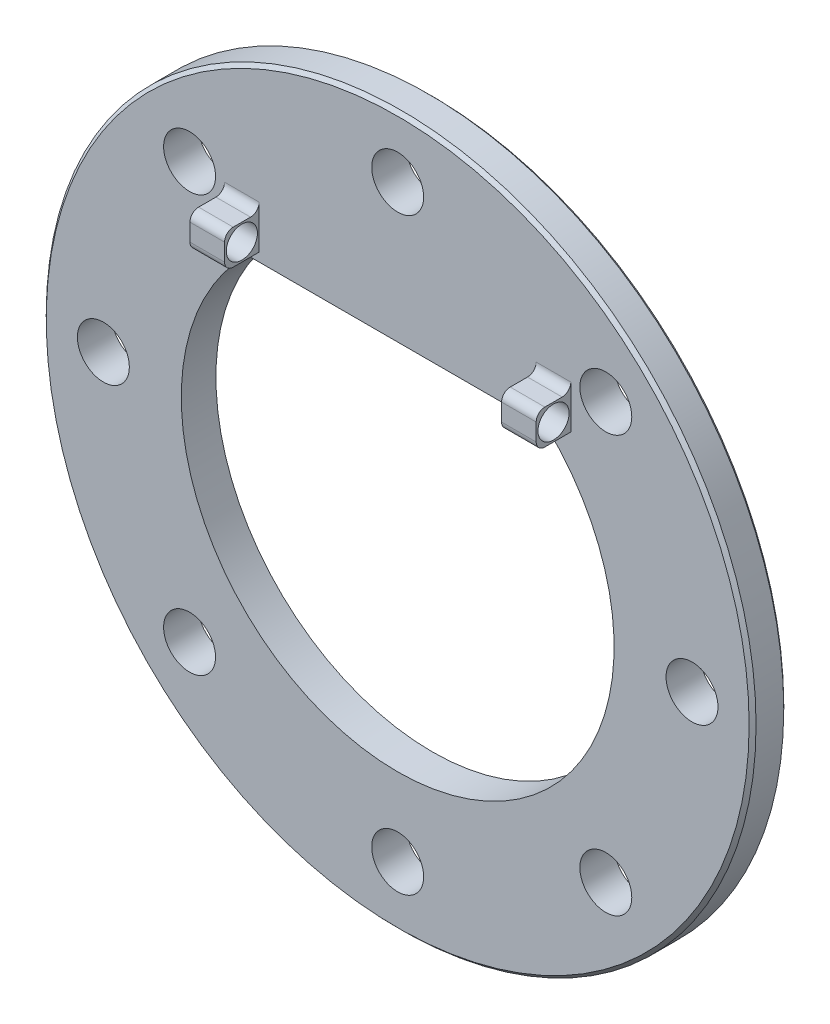
SolidWorks part; units mm, degrees
material "1023 Carbon Steel Sheet (SS)"
ref_plane "Front Plane" through (0, 0, 0) normal (0, 0, 1) x (1, 0, 0)
ref_plane "Top Plane" through (0, 0, 0) normal (0, 1, 0) x (1, 0, 0)
ref_plane "Right Plane" through (0, 0, 0) normal (1, 0, 0) x (0, 0, -1)
sketch "Sketch1" plane through (0, 0, 0) normal (0, 0, 1) x (1, 0, 0)
  circle A0 centre (0, 0) radius 205
  circle A1 centre (0, 170) radius 15
  circle A2 centre (120.2082, 120.2082) radius 15
  circle A3 centre (170, 0) radius 15
  circle A4 centre (120.2082, -120.2082) radius 15
  circle A5 centre (0, -170) radius 15
  circle A6 centre (-120.2082, -120.2082) radius 15
  circle A7 centre (-170, 0) radius 15
  circle A8 centre (-120.2082, 120.2082) radius 15
  point P22 (0, 0)
  dimension "D1" = 170
  dimension "D2" = 30
  dimension "D4" = 410
  dimension "D3" = 8
extrude "Boss-Extrude1" add sketch "Sketch1" along normal blind 20 contours A0
chamfer "Chamfer1" distance 2 angle 45 2 edges at (205, 0, 0) (205, 0, 20)
sketch "Sketch2" plane through (0, 0, 20) normal (0, 0, 1) x (1, 0, 0)
  line L0 (-86.7468, 90) -> (86.7468, 90)
  arc A0 (-86.7468, 90) -> (86.7468, 90) centre (0, 0) ccw
  dimension "D1" = 250
  dimension "D2" = 90
extrude "Cut-Extrude1" cut sketch "Sketch2" against normal up to surface (20 mm away) up to face at (203, 0, 0)
sketch "Sketch4" plane through (0, 0, 20) normal (0, 0, 1) x (1, 0, 0)
  line L1 (-100, 95) -> (-80, 95)
  line L2 (-100, 95) -> (-100, 115)
  line L3 (-100, 115) -> (-80, 115)
  line L4 (100, 95) -> (100, 115)
  line L5 (0, 0) -> (0, 136.6258) construction
  line L6 (80, 115) -> (80, 95)
  line L7 (-80, 115) -> (-80, 95)
  line L8 (80, 115) -> (100, 115)
  line L9 (80, 95) -> (100, 95)
  line L10 (86.7468, 90) -> (-86.7468, 90) construction
  dimension "D1" = 20
  dimension "D2" = 200
  dimension "D3" = 20
  dimension "D4" = 5
extrude "Boss-Extrude2" add sketch "Sketch4" along normal blind 20
sketch "Sketch5" plane through (0, 0, 0) normal (1, 0, 0) x (0, 0, -1)
  line L0 (-40, 105) -> (-30, 105) construction
  line L1 (-40, 95) -> (-40, 115) construction
  line L2 (-30, 105) -> (-20, 105) construction
  line L3 (-20, 95) -> (-20, 115) construction
  circle A0 centre (-30, 105) radius 9
  dimension "D1" = 18
extrude "Cut-Extrude3" cut sketch "Sketch5" against normal up to surface and the other way up to surface up to face at (-100, 105, 30) other way up to face at (100, 105, 30)
fillet "Fillet1" radius 5 6 edges at (-90, 95, 40) (-90, 115, 20) (-90, 115, 40) (90, 115, 20) (90, 95, 40) (90, 115, 40)
